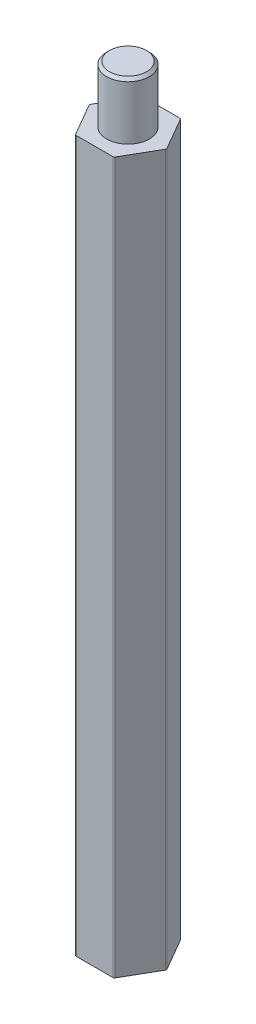
SolidWorks part; units mm, degrees
material "黄铜"
ref_plane "前视基准面" through (0, 0, 0) normal (0, 0, 1) x (1, 0, 0)
ref_plane "上视基准面" through (0, 0, 0) normal (0, 1, 0) x (1, 0, 0)
ref_plane "右视基准面" through (0, 0, 0) normal (1, 0, 0) x (0, 0, -1)
sketch "草图1" plane through (0, 0, 0) normal (0, 1, 0) x (1, 0, 0)
  line L1 (2.7135, 0) -> (1.3568, 2.35)
  line L2 (1.3568, 2.35) -> (-1.3568, 2.35)
  line L3 (-1.3568, 2.35) -> (-2.7135, 0)
  line L4 (-2.7135, 0) -> (-1.3568, -2.35)
  line L5 (-1.3568, -2.35) -> (1.3568, -2.35)
  line L6 (1.3568, -2.35) -> (2.7135, 0)
  circle A0 centre (0, 0) radius 2.35 construction
  dimension "D1" = 4.7
extrude "凸台-拉伸1" add sketch "草图1" along normal blind 50
sketch "草图2" plane through (0, 50, 0) normal (0, 1, 0) x (1, 0, 0)
  circle A0 centre (0, 0) radius 1.5
  dimension "D1" = 3
extrude "凸台-拉伸2" add sketch "草图2" along normal blind 4
cosmetic thread "装饰螺纹线1" parameters "D2"=2.459
sketch "草图3" plane through (0, 0, 0) normal (0, -1, 0) x (1, 0, 0)
  circle A0 centre (0, 0) radius 1.5
  dimension "D1" = 3
extrude "切除-拉伸1" cut sketch "草图3" against normal blind 4
cosmetic thread "装饰螺纹线2" parameters "D2"=4
chamfer "倒角1" distance 0.2 angle 45 2 edges at (0, 4, -1.5) (0, 54, 1.5)
fillet "圆角1" radius 0.1 6 edges at (1.3568, 25, 2.35) (-1.3568, 25, 2.35) (-2.7135, 25, 0) (-1.3568, 25, -2.35) (1.3568, 25, -2.35) (2.7135, 25, 0)
